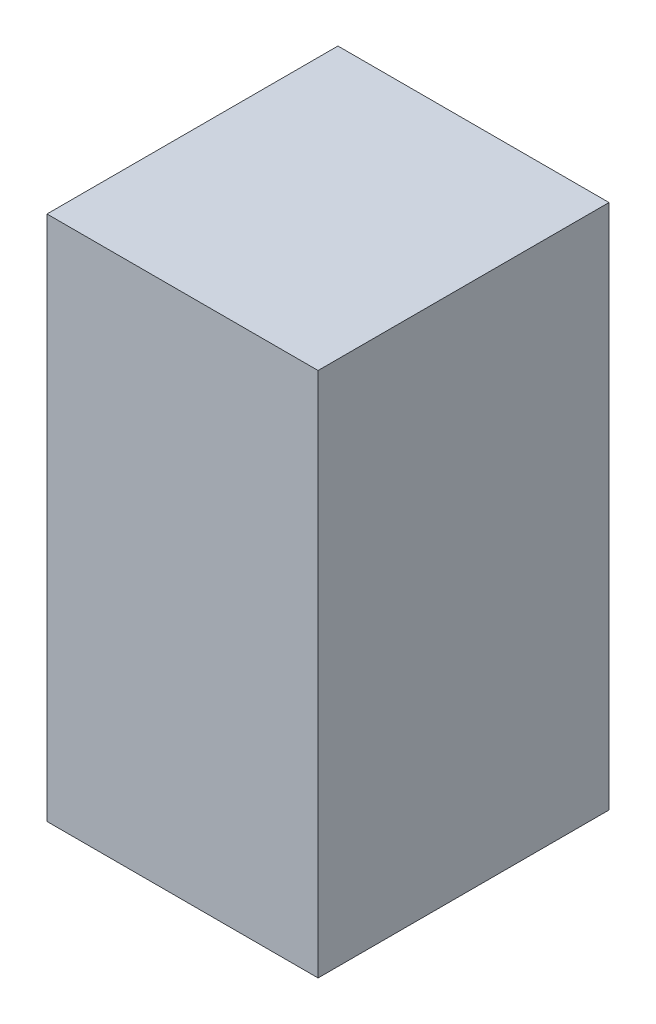
SolidWorks part; units mm, degrees
ref_plane "Front Plane" through (0, 0, 0) normal (0, 0, 1) x (1, 0, 0)
ref_plane "Top Plane" through (0, 0, 0) normal (0, 1, 0) x (1, 0, 0)
ref_plane "Right Plane" through (0, 0, 0) normal (1, 0, 0) x (0, 0, -1)
sketch "Sketch1" plane through (0, 0, 0) normal (0, 1, 0) x (1, 0, 0)
  line L0 (0, 0) -> (241.8, 0)
  line L1 (241.8, 0) -> (241.8, 259.5)
  line L2 (241.8, 259.5) -> (0, 259.5)
  line L3 (0, 259.5) -> (0, 0)
extrude "Boss-Extrude1" add sketch "Sketch1" along normal blind 469.26
